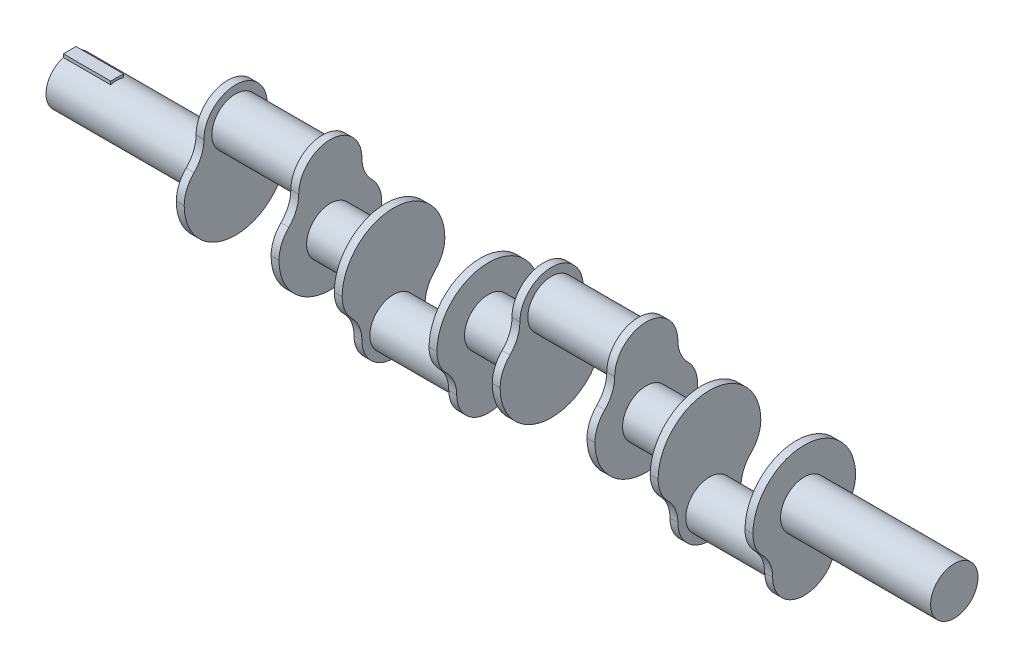
SolidWorks part; units mm, degrees
material "Alloy Steel (SS)"
ref_plane "Front Plane" through (0, 0, 0) normal (0, 0, 1) x (1, 0, 0)
ref_plane "Top Plane" through (0, 0, 0) normal (0, 1, 0) x (1, 0, 0)
ref_plane "Right Plane" through (0, 0, 0) normal (1, 0, 0) x (0, 0, -1)
sketch "Sketch1" plane through (0, 0, 0) normal (1, 0, 0) x (0, 0, -1)
  circle A0 centre (0, 0) radius 15
  dimension "D1" = 30
extrude "Boss-Extrude1" add sketch "Sketch1" along normal blind 320 and the other way blind 240
sketch "Sketch2" plane through (0, 0, 0) normal (0, 1, 0) x (1, 0, 0)
  line L0 (-57.5, 91.6745) -> (-57.5, -91.6745) construction
  line L1 (42.5, 91.6745) -> (42.5, -91.6745) construction
  line L2 (142.5, 91.6745) -> (142.5, -91.6745) construction
  point P6 (42.5, 0)
  point P7 (142.5, 0)
  point P11 (-57.5, 0)
  dimension "D1" = 57.5
  dimension "D2" = 100
  dimension "D3" = 100
ref_plane "Plane1" through (-57.5, 0, 0) normal (1, 0, 0) x (0, 0, -1)
sketch "Sketch3" plane through (-57.5, 0, 0) normal (1, 0, 0) x (0, 0, -1)
  circle A0 centre (0, 30) radius 20 construction
  circle A1 centre (0, 0) radius 32.5 construction
  arc A2 (-32.5, 0) -> (32.5, 0) centre (0, 0) ccw
  arc A3 (20, 30) -> (-20, 30) centre (0, 30) ccw
  arc A4 (-32.5, 0) -> (-26.25, 15) centre (-11.375, 0) cw
  arc A5 (-26.25, 15) -> (-20, 30) centre (-41.125, 30) ccw
  arc A6 (20, 30) -> (26.25, 15) centre (41.125, 30) ccw
  arc A7 (26.25, 15) -> (32.5, 0) centre (11.375, 0) cw
  dimension "D1" = 40
  dimension "D3" = 65
  dimension "D2" = 30
extrude "Boss-Extrude2" add sketch "Sketch3" against normal blind 2.5 and the other way blind 2.5 from offset 20 offset against normal yes
sketch "Sketch4" plane through (-57.5, 0, 0) normal (1, 0, 0) x (0, 0, -1)
  circle A0 centre (0, 0) radius 32.5 construction
  circle A1 centre (0, -30) radius 20 construction
  arc A2 (-32.5, 0) -> (32.5, 0) centre (0, 0) cw
  arc A3 (-20, -30) -> (20, -30) centre (0, -30) ccw
  arc A4 (-20, -30) -> (-26.25, -15) centre (-41.125, -30) ccw
  arc A5 (-26.25, -15) -> (-32.5, 0) centre (-11.375, 0) cw
  arc A6 (20, -30) -> (26.25, -15) centre (41.125, -30) cw
  arc A7 (26.25, -15) -> (32.5, 0) centre (11.375, 0) ccw
  dimension "D2" = 40
  dimension "D3" = 30
ref_plane "Plane2" through (42.5, 0, 0) normal (1, 0, 0) x (0, 0, -1)
extrude "Boss-Extrude4" add sketch "Sketch4" along normal blind 2.5 and the other way blind 2.5 from offset 20
sketch "Sketch5" plane through (42.5, 0, 0) normal (1, 0, 0) x (0, 0, -1)
  arc A0 (-32.5, 0) -> (32.5, 0) centre (0, 0) cw
  arc A1 (32.5, 0) -> (26.25, -15) centre (11.375, 0) cw
  arc A2 (26.25, -15) -> (20, -30) centre (41.125, -30) ccw
  arc A3 (20, -30) -> (-20, -30) centre (0, -30) cw
  arc A4 (-20, -30) -> (-26.25, -15) centre (-41.125, -30) ccw
  arc A5 (-26.25, -15) -> (-32.5, 0) centre (-11.375, 0) cw
extrude "Boss-Extrude5" add sketch "Sketch5" along normal blind 2.5 and the other way blind 2.5 from offset 20 offset against normal yes
sketch "Sketch7" plane through (-35, 0, 0) normal (1, 0, 0) x (0, 0, -1)
  circle A0 centre (0, 0) radius 15
  dimension "D1" = 30
extrude "Cut-Extrude1" cut sketch "Sketch7" along normal up to surface (55 mm away) up to face at (20, 0, 15)
sketch "Sketch6" plane through (-35, 0, 0) normal (1, 0, 0) x (0, 0, -1)
  circle A0 centre (0, -30) radius 15
  dimension "D1" = 30
extrude "Boss-Extrude6" add sketch "Sketch6" along normal up to surface (55 mm away)
sketch "Sketch8" plane through (42.5, 0, 0) normal (1, 0, 0) x (0, 0, -1)
  arc A0 (-20, 30) -> (20, 30) centre (0, 30) cw
  arc A1 (20, 30) -> (26.25, 15) centre (41.125, 30) ccw
  arc A2 (26.25, 15) -> (32.5, 0) centre (11.375, 0) cw
  arc A3 (32.5, 0) -> (-32.5, 0) centre (0, 0) cw
  arc A4 (-32.5, 0) -> (-26.25, 15) centre (-11.375, 0) cw
  arc A5 (-26.25, 15) -> (-20, 30) centre (-41.125, 30) ccw
extrude "Boss-Extrude7" add sketch "Sketch8" along normal blind 2.5 and the other way blind 2.5 from offset 20
ref_plane "Plane3" through (142.5, 0, 0) normal (1, 0, 0) x (0, 0, -1)
sketch "Sketch9" plane through (142.5, 0, 0) normal (1, 0, 0) x (0, 0, -1)
  arc A0 (-20, 30) -> (20, 30) centre (0, 30) cw
  arc A1 (20, 30) -> (26.25, 15) centre (41.125, 30) ccw
  arc A2 (26.25, 15) -> (32.5, 0) centre (11.375, 0) cw
  arc A3 (32.5, 0) -> (-32.5, 0) centre (0, 0) cw
  arc A4 (-32.5, 0) -> (-26.25, 15) centre (-11.375, 0) cw
  arc A5 (-26.25, 15) -> (-20, 30) centre (-41.125, 30) ccw
extrude "Boss-Extrude8" add sketch "Sketch9" along normal blind 2.5 and the other way blind 2.5 from offset 20 offset against normal yes
sketch "Sketch11" plane through (65, 0, 0) normal (1, 0, 0) x (0, 0, -1)
  line L0 (91.6745, 0) -> (-91.6745, 0) construction
  circle A0 centre (0, 0) radius 15
  dimension "D1" = 30
extrude "Cut-Extrude2" cut sketch "Sketch11" along normal up to surface (55 mm away) up to face at (120, 0, -15)
sketch "Sketch10" plane through (65, 0, 0) normal (1, 0, 0) x (0, 0, -1)
  circle A0 centre (0, 30) radius 15
  dimension "D1" = 30
extrude "Boss-Extrude11" add sketch "Sketch10" along normal up to next
sketch "Sketch12" plane through (142.5, 0, 0) normal (1, 0, 0) x (0, 0, -1)
  arc A0 (-20, -30) -> (20, -30) centre (0, -30) ccw
  arc A1 (20, -30) -> (26.25, -15) centre (41.125, -30) cw
  arc A2 (26.25, -15) -> (32.5, 0) centre (11.375, 0) ccw
  arc A3 (32.5, 0) -> (-32.5, 0) centre (0, 0) ccw
  arc A4 (-32.5, 0) -> (-26.25, -15) centre (-11.375, 0) ccw
  arc A5 (-26.25, -15) -> (-20, -30) centre (-41.125, -30) cw
extrude "Boss-Extrude12" add sketch "Sketch12" along normal blind 2.5 and the other way blind 2.5 from offset 20
sketch "Sketch13" plane through (142.5, 0, 0) normal (1, 0, 0) x (0, 0, -1)
  arc A0 (-32.5, 0) -> (32.5, 0) centre (0, 0) cw
  arc A1 (-32.5, 0) -> (-26.25, -15) centre (-11.375, 0) ccw
  arc A2 (-26.25, -15) -> (-20, -30) centre (-41.125, -30) cw
  arc A3 (-20, -30) -> (20, -30) centre (0, -30) ccw
  circle A6 centre (0, 0) radius 32.5 construction
  circle A7 centre (0, -30) radius 20 construction
  arc A8 (-20, -30) -> (-26.25, -15) centre (-41.125, -30) ccw construction
  arc A9 (32.5, 0) -> (26.25, -15) centre (11.375, 0) cw
  arc A10 (26.25, -15) -> (20, -30) centre (41.125, -30) ccw
extrude "Boss-Extrude13" add sketch "Sketch13" along normal blind 2.5 and the other way blind 2.5 from offset 80
sketch "Sketch15" plane through (165, 0, 0) normal (1, 0, 0) x (0, 0, -1)
  line L0 (91.6745, 0) -> (-91.6745, 0) construction
  circle A0 centre (0, 0) radius 15
  dimension "D1" = 30
extrude "Cut-Extrude3" cut sketch "Sketch15" along normal up to surface (55 mm away) up to face at (220, 0, -15)
sketch "Sketch14" plane through (165, 0, 0) normal (1, 0, 0) x (0, 0, -1)
  circle A0 centre (0, -30) radius 15
  dimension "D1" = 30
extrude "Boss-Extrude14" add sketch "Sketch14" along normal up to next
sketch "Sketch17" plane through (-57.5, 0, 0) normal (1, 0, 0) x (0, 0, -1)
  arc A0 (-20, 30) -> (20, 30) centre (0, 30) cw
  arc A6 (-20, 30) -> (-26.25, 15) centre (-41.125, 30) cw
  arc A7 (-26.25, 15) -> (-32.5, 0) centre (-11.375, 0) ccw
  arc A8 (-32.5, 0) -> (32.5, 0) centre (0, 0) ccw
  arc A9 (32.5, 0) -> (26.25, 15) centre (11.375, 0) ccw
  arc A10 (26.25, 15) -> (20, 30) centre (41.125, 30) cw
extrude "Boss-Extrude15" add sketch "Sketch17" along normal blind 2.5 and the other way blind 2.5 from offset 80 offset against normal yes
sketch "Sketch19" plane through (-135, 0, 0) normal (1, 0, 0) x (0, 0, -1)
  circle A0 centre (0, 0) radius 15
  dimension "D1" = 30
extrude "Cut-Extrude4" cut sketch "Sketch19" along normal up to surface (55 mm away) up to face at (-80, 0, 15)
sketch "Sketch18" plane through (-135, 0, 0) normal (1, 0, 0) x (0, 0, -1)
  circle A0 centre (0, 30) radius 15
  dimension "D1" = 30
extrude "Boss-Extrude16" add sketch "Sketch18" along normal up to next
hole_wizard "Tap Drill for M12 Tap1" positions "Sketch21" profile "Sketch22" hole size "M12" standard "ISO"
sketch "Sketch21" plane through (-240, 0, 0) normal (-1, 0, 0) x (0, 0, 1)
  point P0 (0, 0)
sketch "Sketch22" plane through (-240, 0, 0) normal (0, 1, 0) x (0, 0, 1)
  line L0 (0, 0) -> (0, 33.0644)
  line L1 (0, 33.0644) -> (5.1, 30)
  line L2 (5.1, 30) -> (5.1, 0)
  line L5 (5.1, 0) -> (0, 0)
  line L10 (0, 33.0644) -> (-5.1, 30) construction
  line L11 (0, -6.35) -> (0, 107.95) construction
  dimension "Hole Dia." = 10.2
  dimension "Hole Depth" = 30
  dimension "Drill Angle" = 118
sketch "Sketch23" plane through (-240, 0, 0) normal (-1, 0, 0) x (0, 0, 1)
  line L1 (-4, 10.5) -> (4, 10.5)
  line L2 (-4, 10.5) -> (-4, 16.5)
  line L3 (-4, 16.5) -> (4, 16.5)
  line L4 (4, 10.5) -> (4, 16.5)
  point P4 (0, 10.5)
  dimension "D1" = 8
  dimension "D2" = 16.5
  dimension "D3" = 6
extrude "Boss-Extrude17" add sketch "Sketch23" against normal blind 30
